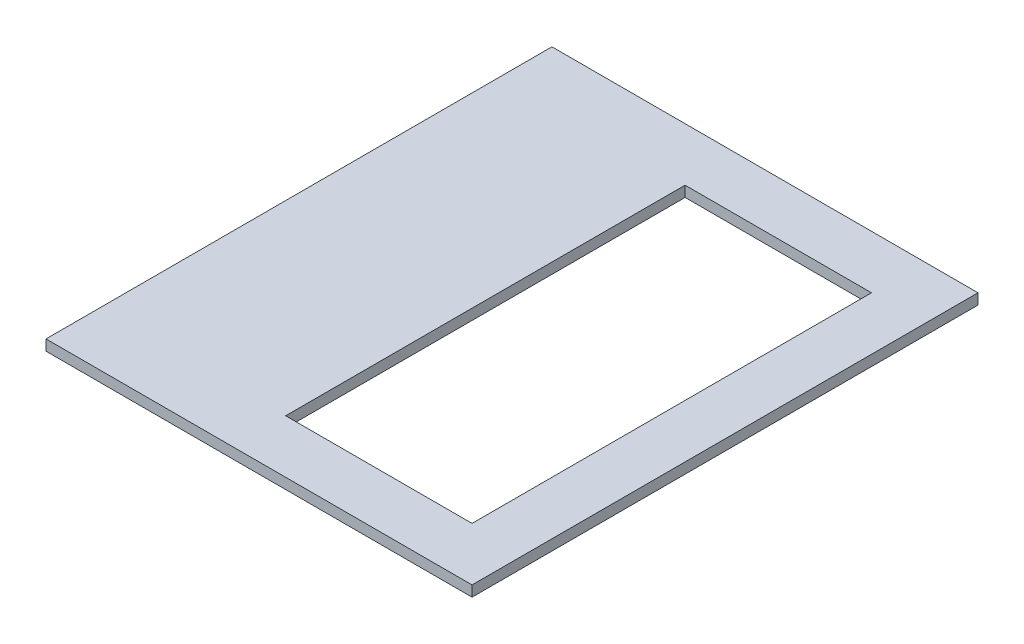
SolidWorks part; units mm, degrees
ref_plane "Front Plane" through (0, 0, 0) normal (0, 0, 1) x (1, 0, 0)
ref_plane "Top Plane" through (0, 0, 0) normal (0, 1, 0) x (1, 0, 0)
ref_plane "Right Plane" through (0, 0, 0) normal (1, 0, 0) x (0, 0, -1)
sketch "Sketch1" plane through (0, 0, 0) normal (0, 1, 0) x (1, 0, 0)
  line L0 (-55, 95) -> (55, 95)
  line L1 (-35, 75) -> (35, 75)
  line L2 (-35, 75) -> (-35, -75)
  line L3 (-35, -75) -> (35, -75)
  line L4 (35, 75) -> (35, -75)
  line L5 (-35, 75) -> (35, -75) construction
  line L6 (-35, -75) -> (35, 75) construction
  line L7 (55, 95) -> (55, -95)
  line L8 (-55, -95) -> (55, -95)
  line L9 (-55, 95) -> (-105, 95)
  line L10 (-55, 95) -> (-55, -95) construction
  line L11 (-105, 95) -> (-105, -95)
  line L12 (-105, -95) -> (-55, -95)
  point P0 (0, 0)
  dimension "D1" = 20
  dimension "D2" = 70
extrude "Boss-Extrude1" add sketch "Sketch1" along normal blind 4
